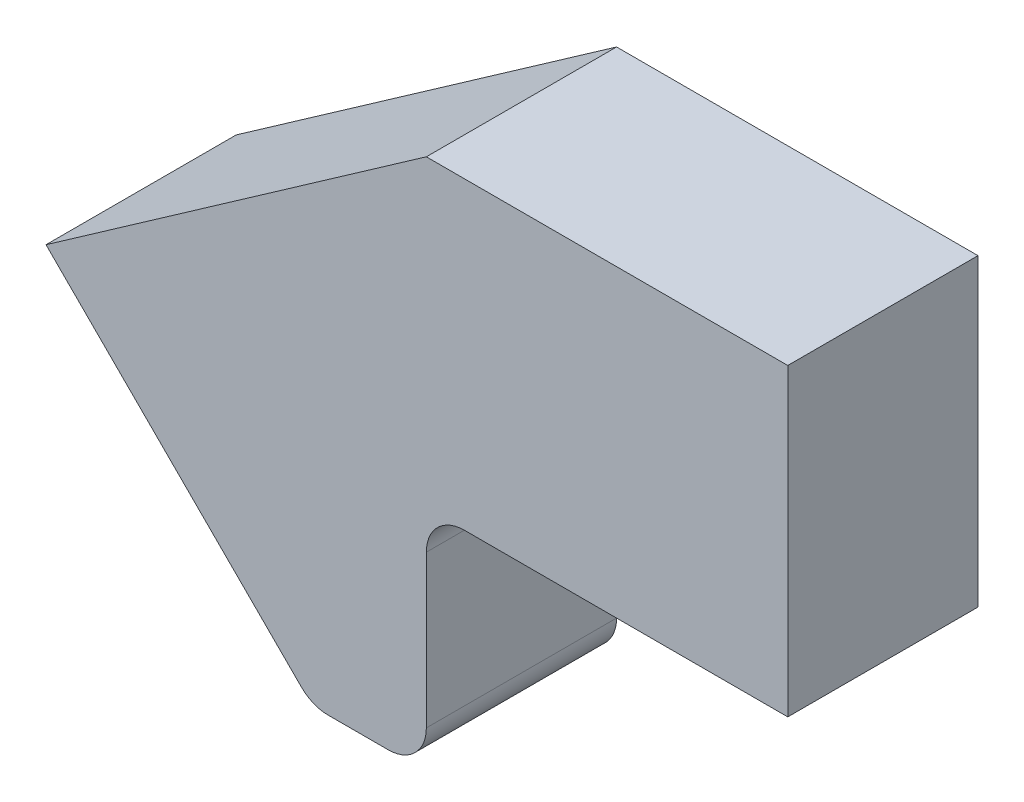
SolidWorks part; units mm, degrees
material "PBT General Purpose"
ref_plane "Front Plane" through (0, 0, 0) normal (0, 0, 1) x (1, 0, 0)
ref_plane "Top Plane" through (0, 0, 0) normal (0, 1, 0) x (1, 0, 0)
ref_plane "Right Plane" through (0, 0, 0) normal (1, 0, 0) x (0, 0, -1)
sketch "frame_outline" plane through (0, 0, 0) normal (0, 0, 1) x (1, 0, 0)
  line L80 (0, 0) -> (0.4999, 0.35)
  line L83 (0.4999, 0.35) -> (0.9749, 0.35)
  line L84 (0.9749, 0.35) -> (0.9749, -0.05)
  line L85 (0.9749, -0.05) -> (0.4999, -0.05)
  line L86 (0.4999, -0.05) -> (0.4999, -0.35)
  line L87 (0.4999, -0.35) -> (0.35, -0.35)
  line L88 (0.35, -0.35) -> (0, 0)
  line L89 (0, 0) -> (0.6325, 0) construction
  dimension "D18" = 0.4
  dimension "D20" = 0.3
  dimension "D23" = 35
  dimension "D21" = 0.475
  dimension "D22" = 45
  dimension "D3" = 0.475
  dimension "D4" = 0.05
  dimension "D5" = 0.6102
extrude "Boss-Extrude1" add sketch "frame_outline" along normal mid plane 0.25
fillet "Fillet1" radius 0.05 3 edges at (0.4999, -0.35, 0) (0.4999, -0.05, 0) (0.35, -0.35, 0)
equation "\"t\"= 0.25'thickness of the sheets"
equation "\"t_cf\"= 0.115'thickness of single carbon fiber layer"
equation "\"t_kapton\"= 0.025'thickness of single Kapton flex layer"
equation "\"t_fr4\"= 0.1'thickness of FR4 with copper layer"
equation "\"joint_flex\"= 0.1'Width of flextures gap"
equation "\"joint_flex_eff\"= 0.02'Width of flecture after castelation"
equation "\"joint_fold\"= 0.2'Width of folding joints for 90deg fold"
equation "\"gap_tolerance\"= 0.002'Width to have interfecence fit between carbon fiber inserts"
equation "\"assemble_angle\"= 90'Angle of assembly parts"
equation "\"D1@Boss-Extrude1\"=\"t\""
equation "\"link_lift\"= 0.5'Actuation linkage amplification for the lift motion"
equation "\"link_swing\"= 0.45'Actuation linkage amplification for the swing motion"
equation "\"D21@frame_outline\"=1.05+ \"joint_flex\"/2 -\"link_lift\"-\"t\"/2"
equation "\"D3@frame_outline\"=\"t\"*2.5-\"joint_fold\"+0.05"
